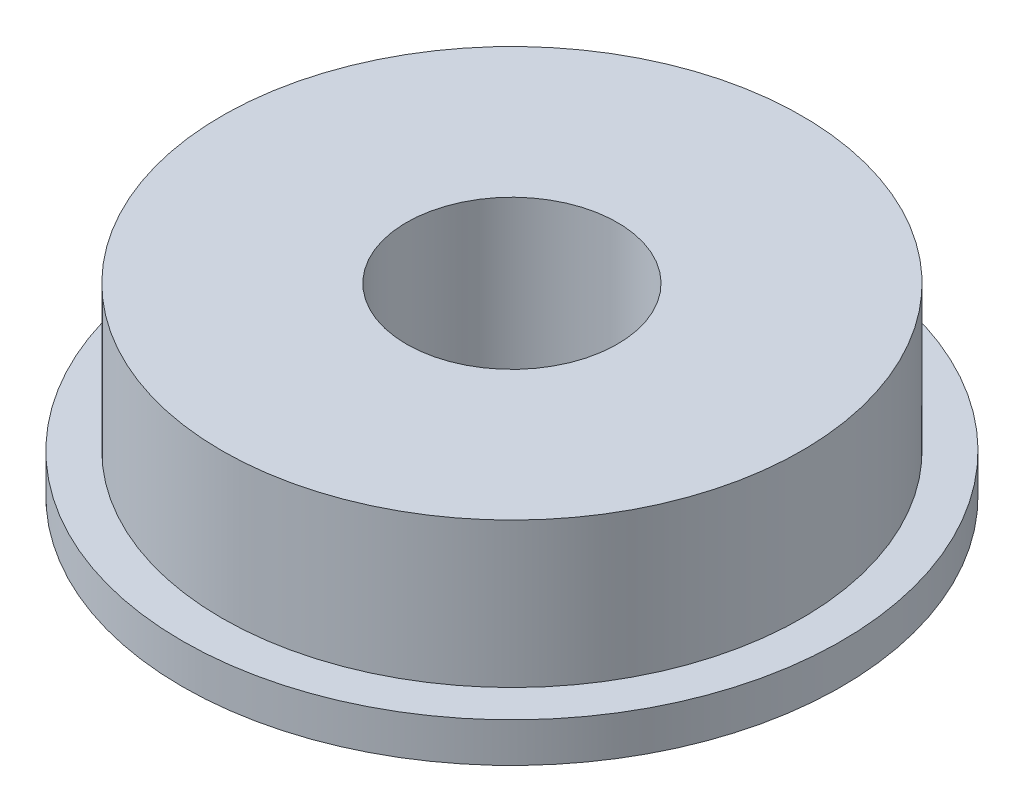
SolidWorks part; units mm, degrees
ref_plane "Front Plane" through (0, 0, 0) normal (0, 0, 1) x (1, 0, 0)
ref_plane "Top Plane" through (0, 0, 0) normal (0, 1, 0) x (1, 0, 0)
ref_plane "Right Plane" through (0, 0, 0) normal (1, 0, 0) x (0, 0, -1)
sketch "Sketch1" plane through (0, 0, 0) normal (0, 1, 0) x (1, 0, 0)
  circle A0 centre (0, 0) radius 12.5
  dimension "D1" = 25
extrude "Boss-Extrude1" add sketch "Sketch1" along normal blind 1.5
sketch "Sketch2" plane through (0, 1.5, 0) normal (0, 1, 0) x (1, 0, 0)
  circle A0 centre (0, 0) radius 11
  dimension "D1" = 22
extrude "Boss-Extrude2" add sketch "Sketch2" along normal blind 5.5
hole_wizard "Ø8.0 (8) Diameter Hole1" positions "Sketch3" profile "Sketch4" hole size "Ø8.0" standard "ISO" end condition up to next
sketch "Sketch3" plane through (0, 7, 0) normal (0, 1, 0) x (1, 0, 0)
  point P0 (0, 0)
sketch "Sketch4" plane through (0, 7, 0) normal (1, 0, 0) x (0, 0, 1)
  line L0 (0, 0) -> (0, 7)
  line L1 (0, 7) -> (4, 7)
  line L2 (4, 7) -> (4, 0)
  line L5 (4, 0) -> (0, 0)
  line L11 (0, -6.35) -> (0, 107.95) construction
  dimension "Thru Hole Dia." = 8
  dimension "Thru Hole Depth" = 7
